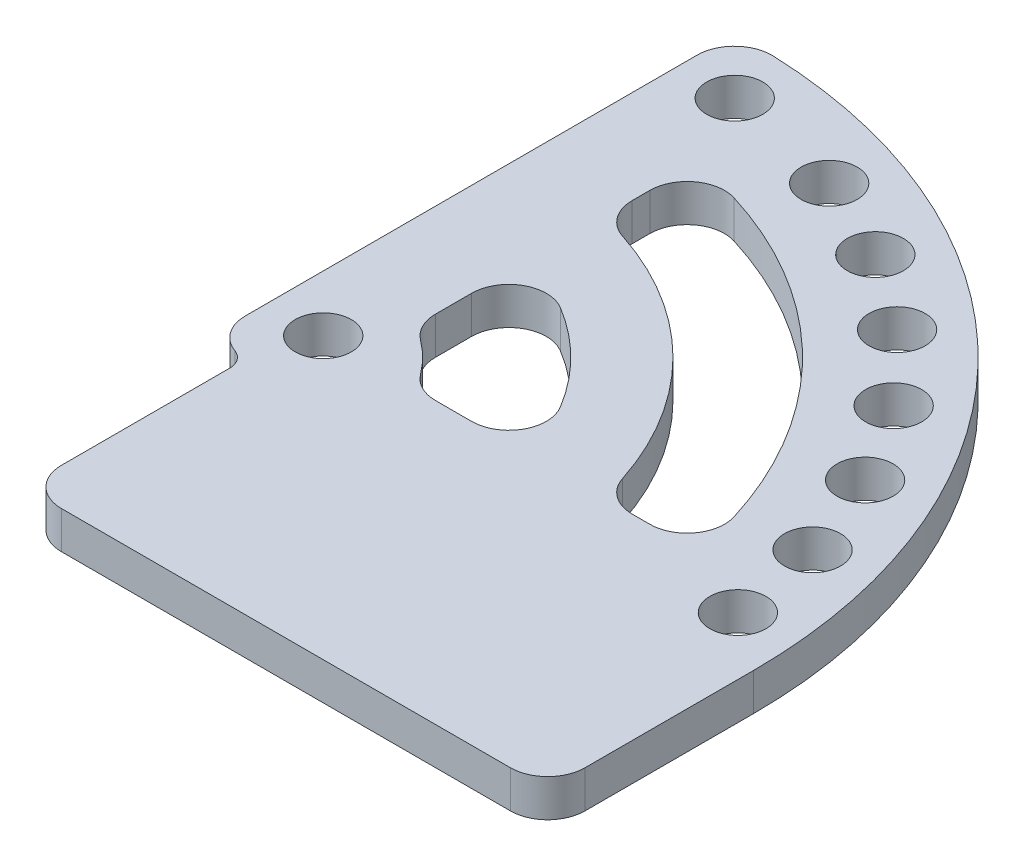
SolidWorks part; units mm, degrees
ref_plane "前视基准面" through (0, 0, 0) normal (0, 0, 1) x (1, 0, 0)
ref_plane "上视基准面" through (0, 0, 0) normal (0, 1, 0) x (1, 0, 0)
ref_plane "右视基准面" through (0, 0, 0) normal (1, 0, 0) x (0, 0, -1)
other "Configuration Table"
sketch "草图1" plane through (0, 0, 0) normal (0, 1, 0) x (1, 0, 0)
  line L0 (-11, 0) -> (0, 0)
  line L1 (0, 0) -> (11, 0)
  line L3 (-11, 11) -> (11, 11) construction
  line L4 (11, 11) -> (11, 0) construction
  line L5 (-15, 11) -> (-11, 11) construction
  line L7 (-15, 37) -> (-15, 15) construction
  line L8 (11, 0) -> (14, 0)
  line L9 (14, 0) -> (14, 11)
  line L10 (-15, 40) -> (-15, 37) construction
  line L12 (-14, 0) -> (-11, 0)
  line L13 (-15, 11) -> (-15, 15) construction
  line L14 (-16, 12) -> (-15, 12)
  line L15 (-15, 40) -> (-16, 40)
  line L16 (-16, 40) -> (-16, 12)
  line L17 (-15, 11) -> (10.9011, 13.266) construction
  line L18 (-15, 11) -> (-12.4725, 39.8896) construction
  line L19 (-14, 11) -> (-14, 0)
  line L20 (-11, 11) -> (-11, 0) construction
  line L21 (-11, 24) -> (-11, 17.9282)
  line L22 (-8.0718, 15) -> (-2, 15)
  line L23 (-11, 28) -> (-11, 33)
  line L24 (2, 15) -> (7, 15)
  line L25 (-15, 11) -> (9.9928, 18.1666) construction
  line L26 (-15, 15) -> (-13, 15) construction
  line L27 (-13, 15) -> (-13, 37) construction
  line L28 (-13, 37) -> (-15, 37) construction
  arc A0 (-11, 11) -> (-15, 15) centre (-15, 11) ccw construction
  arc A1 (11, 11) -> (-15, 37) centre (-15, 11) ccw construction
  arc A2 (14, 11) -> (-15, 40) centre (-15, 11) ccw
  circle A3 centre (10.9011, 13.266) radius 1.5
  circle A4 centre (9.9928, 18.1666) radius 1.5
  circle A5 centre (8.1662, 22.8038) radius 1.5
  circle A6 centre (5.4883, 27.0072) radius 1.5
  circle A7 centre (2.0575, 30.6224) radius 1.5
  circle A8 centre (-2, 33.5167) radius 1.5
  circle A9 centre (-6.5352, 35.5835) radius 1.5
  arc A11 (-15, 12) -> (-14, 11) centre (-15, 11) cw
  arc A14 (-11, 17.9282) -> (-8.0718, 15) centre (-15, 11) cw
  arc A15 (-11, 24) -> (-2, 15) centre (-15, 11) cw
  arc A16 (-11, 28) -> (2, 15) centre (-15, 11) cw
  arc A17 (-11, 33) -> (7, 15) centre (-15, 11) cw
  circle A18 centre (-11.3815, 36.747) radius 1.5 [skipped]
  circle A19 centre (-13, 15) radius 1.5
  circle A20 centre (-13, 37) radius 1.5
  point P9 (-15, 26)
  point P23 (-15, 26)
  dimension "D4" = 16
  dimension "D5" = 3
  dimension "D9" = 4
  dimension "D10" = 3
  dimension "D11" = 4
  dimension "D14" = 8
  dimension "D1" = 22
  dimension "D2" = 26
  dimension "D3" = 3
  dimension "D6" = 5
  dimension "D8" = 5
  dimension "D12" = 4
  dimension "D13" = 2
  dimension "D15" = 2
  dimension "D16" = 7
  dimension "D17" = 11
  dimension "D18" = 2
  dimension "D7" = 8
extrude "凸台-拉伸1" add sketch "草图1" along normal blind 2
fillet "圆角1" radius 2 12 edges at (-14, 1, 0) (-16, 1, -12) (-16, 1, -40) (14, 1, 0) (-11, 1, -17.9282) (-8.0718, 1, -15) (-2, 1, -15) (-11, 1, -24) (7, 1, -15) (-11, 1, -28) (2, 1, -15) (-11, 1, -33)
